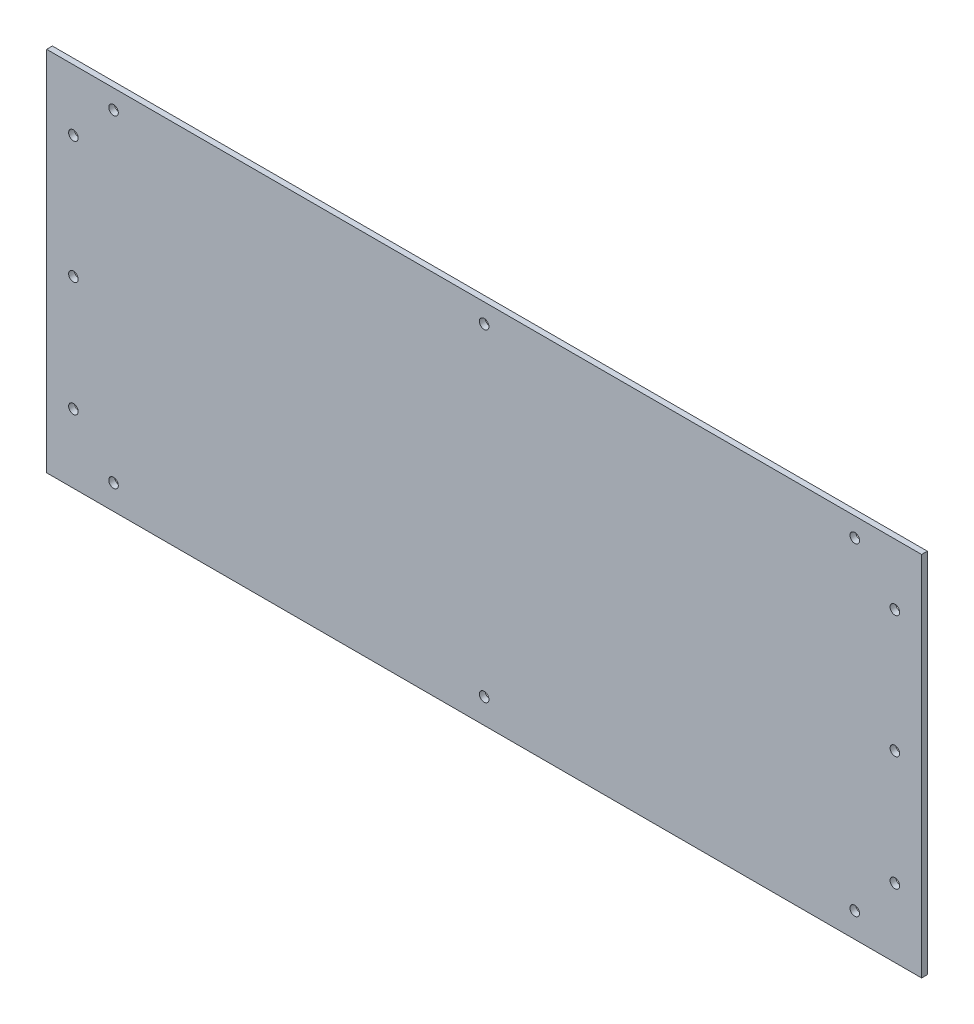
SolidWorks part; units mm, degrees
material "1345 Alloy"
ref_plane "Front Plane" through (0, 0, 0) normal (0, 0, 1) x (1, 0, 0)
ref_plane "Top Plane" through (0, 0, 0) normal (0, 1, 0) x (1, 0, 0)
ref_plane "Right Plane" through (0, 0, 0) normal (1, 0, 0) x (0, 0, -1)
sketch "Sketch1" plane through (0, 0, 0) normal (0, 0, 1) x (1, 0, 0)
  line L1 (-229, 96) -> (229, 96)
  line L2 (-229, 96) -> (-229, -96)
  line L3 (-229, -96) -> (229, -96)
  line L4 (229, 96) -> (229, -96)
  line L5 (-229, 96) -> (229, -96) construction
  line L6 (-229, -96) -> (229, 96) construction
  point P0 (0, 0)
  dimension "D1" = 458
  dimension "D2" = 192
extrude "Boss-Extrude1" add sketch "Sketch1" along normal blind 3
sketch "Sketch2" plane through (0, 0, 3) normal (0, 0, 1) x (1, 0, 0)
  line L0 (-229, 96) -> (-229, 86) construction
  line L1 (-229, 96) -> (-194, 96) construction
  line L2 (-194, 96) -> (-194, 86) construction
  line L3 (-194, 86) -> (-229, 86) construction
  line L4 (-194, -83.0046) -> (194, -83.0046) construction
  line L6 (0, -83) -> (0, -96) construction
  line L7 (194, -96.0046) -> (194, -83.0046) construction
  line L8 (194, 86) -> (194, 96) construction
  line L9 (-229, 0) -> (-215, 0) construction
  line L10 (-215, 0) -> (-215, 64) construction
  line L11 (-215, 0) -> (-215, -60) construction
  line L12 (229, 0) -> (215, 0) construction
  line L13 (0, 86) -> (-194, 86) construction
  line L14 (215, 64) -> (215, 96) construction
  line L15 (215, 0) -> (215, 64) construction
  line L16 (215, 0) -> (215, -60) construction
  line L17 (0, 86) -> (194, 86) construction
  line L18 (229, 96) -> (-229, 96) construction
  line L19 (-229, -96) -> (229, -96) construction
  line L22 (-215, 64) -> (-215, 96) construction
  circle A0 centre (-194, 86) radius 2.5
  circle A1 centre (-194, -83.0046) radius 2.5
  circle A2 centre (194, -83.0046) radius 2.5
  circle A3 centre (194, 86) radius 2.5
  circle A4 centre (-215, 0) radius 2.5
  circle A5 centre (-215, -60) radius 2.5
  circle A6 centre (-215, 64) radius 2.5
  circle A7 centre (215, 0) radius 2.5
  circle A8 centre (215, -60) radius 2.5
  circle A9 centre (215, 64) radius 2.5
  circle A10 centre (0, 86) radius 2.5
  circle A11 centre (0, -83) radius 2.5
  dimension "D3" = 5
  dimension "D6" = 5
  dimension "D7" = 5
  dimension "D8" = 5
  dimension "D13" = 5
  dimension "D14" = 5
  dimension "D15" = 5
  dimension "D19" = 5
  dimension "D20" = 5
  dimension "D1" = 10
  dimension "D2" = 35
  dimension "D4" = 13
  dimension "D5" = 12.9954
  dimension "D9" = 13
  dimension "D10" = 14
  dimension "D11" = 64
  dimension "D12" = 60
  dimension "D16" = 14
  dimension "D17" = 64
  dimension "D18" = 60
  dimension "D22" = 194
  dimension "D23" = 194
  dimension "D24" = 32
  dimension "D25" = 32
extrude "Cut-Extrude1" cut sketch "Sketch2" against normal through all
